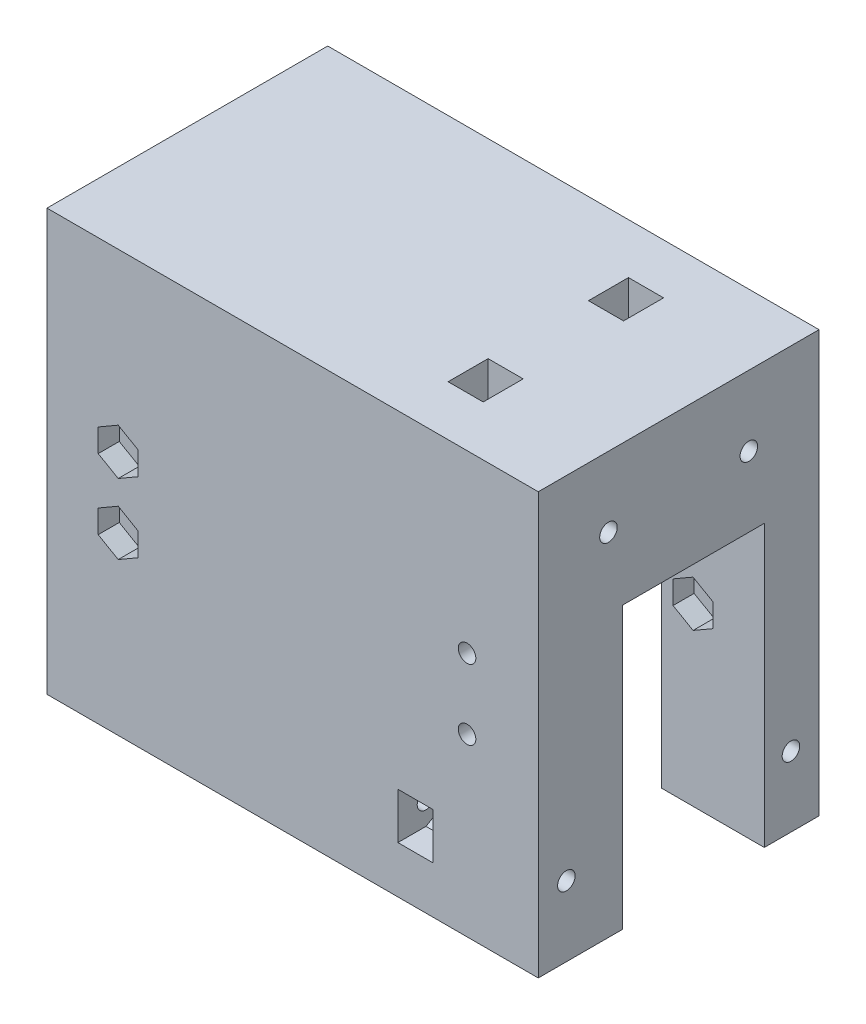
SolidWorks part; units mm, degrees
ref_plane "正面" through (0, 0, 0) normal (0, 0, 1) x (1, 0, 0)
ref_plane "平面" through (0, 0, 0) normal (0, 1, 0) x (1, 0, 0)
ref_plane "右側面" through (0, 0, 0) normal (1, 0, 0) x (0, 0, -1)
sketch "ｽｹｯﾁ2" plane through (0, 0, 0) normal (0, 0, 1) x (1, 0, 0)
  line L1 (-35, 30) -> (35, 30)
  line L2 (-35, 30) -> (-35, -30)
  line L3 (-35, -30) -> (35, -30)
  line L4 (35, 30) -> (35, -30)
  line L5 (-35, 30) -> (35, -30) construction
  line L6 (-35, -30) -> (35, 30) construction
  line L11 (-1.1602, 0.9945) -> (26.8884, -23.0472) construction
  line L12 (-15.8388, -9.5033) -> (15.8388, 9.5033) construction
  point P0 (0, 0)
  point P6 (0, 0)
  dimension "D1" = 70
  dimension "D2" = 60
extrude "ﾎﾞｽ - 押し出し2" add sketch "ｽｹｯﾁ2" along normal blind 40
sketch "ｽｹｯﾁ3" plane through (0, 0, 0) normal (0, 0, 1) x (1, 0, 0)
  line L1 (-20.35, 10.25) -> (20.35, 10.25)
  line L2 (-20.35, 10.25) -> (-20.35, -10.25)
  line L3 (-20.35, -10.25) -> (20.35, -10.25)
  line L4 (20.35, 10.25) -> (20.35, -10.25)
  line L5 (-20.35, 10.25) -> (20.35, -10.25) construction
  line L6 (-20.35, -10.25) -> (20.35, 10.25) construction
  point P0 (0, 0)
  dimension "D1" = 40.7
  dimension "D2" = 20.5
extrude "ｶｯﾄ - 押し出し1" cut sketch "ｽｹｯﾁ3" along normal blind 28 contours L2 L1 L4 L3
sketch "ｽｹｯﾁ4" plane through (0, 0, 0) normal (0, 0, 1) x (1, 0, 0)
  line L0 (20.35, 10.25) -> (35, 10.25)
  line L1 (35, -30) -> (35, 30) construction
  line L2 (35, 10.25) -> (35, -10.25)
  line L3 (35, -10.25) -> (20.35, -10.25)
  line L4 (20.35, -10.25) -> (20.35, 10.25)
extrude "ﾎﾞｽ - 押し出し3" add sketch "ｽｹｯﾁ4" along normal blind 28
sketch "ｽｹｯﾁ5" plane through (0, 0, 0) normal (0, 0, 1) x (1, 0, 0)
  line L0 (20.35, 10.25) -> (35, 10.25)
  line L1 (35, -30) -> (35, 30) construction
  line L2 (35, 10.25) -> (35, -10.25)
  line L3 (35, -10.25) -> (20.35, -10.25)
  line L4 (20.35, -10.25) -> (20.35, 10.25)
sketch "ｽｹｯﾁ6" plane through (0, 0, 0) normal (0, 0, 1) x (1, 0, 0)
  line L0 (-25, -30) -> (-25, -25)
  line L1 (-35, -30) -> (35, -30) construction
  line L2 (-25, -25) -> (-15, -25)
  line L3 (-15, -25) -> (-15, -30)
  line L4 (-15, -30) -> (-25, -30)
  line L5 (15, -25) -> (15, -30)
  line L6 (15, -30) -> (25, -30)
  line L7 (25, -30) -> (25, -25)
  line L8 (25, -25) -> (15, -25)
  dimension "D1" = 15
  dimension "D2" = 10
  dimension "D3" = 15
  dimension "D4" = 10
  dimension "D5" = 5
  dimension "D6" = 5
sketch "ｽｹｯﾁ8" plane through (0, 0, 0) normal (0, 0, 1) x (1, 0, 0)
  line L0 (-25, 30) -> (-25, 25)
  line L1 (35, 30) -> (-35, 30) construction
  line L2 (-25, 25) -> (-15, 25)
  line L3 (-15, 25) -> (-15, 30)
  line L4 (-15, 30) -> (-25, 30)
  line L5 (15, 30) -> (15, 25)
  line L6 (15, 25) -> (25, 25)
  line L7 (25, 25) -> (25, 30)
  line L8 (25, 30) -> (15, 30)
  dimension "D1" = 15
  dimension "D2" = 10
  dimension "D3" = 5
  dimension "D4" = 5
  dimension "D5" = 10
  dimension "D6" = 10
  dimension "D7" = 15
sketch "ｽｹｯﾁ15" plane through (0, 0, 0) normal (0, 0, 1) x (1, 0, 0)
  line L0 (-20.35, 10.25) -> (-20.35, -30)
  line L1 (-15, -30) -> (-25, -30) construction
  line L2 (-20.35, -30) -> (20.35, -30)
  line L3 (15, -30) -> (25, -30) construction
  line L4 (20.35, -30) -> (20.35, 10.25)
  line L5 (20.35, 10.25) -> (-20.35, 10.25)
extrude "ｶｯﾄ - 押し出し6" cut sketch "ｽｹｯﾁ15" along normal blind 28
ref_plane "平面1" through (0, -30, 0) normal (0, -1, 0) x (-1, 0, 0)
sketch "ｽｹｯﾁ16" plane through (0, -30, 0) normal (0, -1, 0) x (-1, 0, 0)
  line L0 (-20.35, -28) -> (-35, -28)
  line L1 (-35, -40) -> (-35, 0) construction
  line L2 (-35, -28) -> (-35, -7.7959)
  line L3 (-35, -7.7959) -> (-20.35, -7.7959)
  line L4 (-20.35, -28) -> (-20.35, 0) construction
  line L5 (-20.35, -7.7959) -> (-20.35, -28)
extrude "ｶｯﾄ - 押し出し7" cut sketch "ｽｹｯﾁ16" against normal blind 40
hole_wizard "M3x0.5 ねじ穴2" positions "ｽｹｯﾁ12" profile "ｽｹｯﾁ13" tap size "M3x0.5" standard "JIS" end condition through all
sketch "ｽｹｯﾁ12" plane through (0, 0, 0) normal (0, 0, -1) x (-1, 0, 0)
  line L0 (20.35, 10.25) -> (20.35, -30) construction
  point P0 (24.85, 5)
  point P2 (24.85, -5)
  dimension "D1" = 10
  dimension "D2" = 5
  dimension "D3" = 24.85
  dimension "D4" = 4.5
sketch "ｽｹｯﾁ13" plane through (-24.85, 5, 0) normal (1, 0, 0) x (0, 1, 0)
  line L0 (0, 0) -> (0, 40)
  line L1 (0, 40) -> (1.25, 40)
  line L2 (1.25, 40) -> (1.25, 0)
  line L5 (1.25, 0) -> (0, 0)
  line L11 (0, -6.35) -> (0, 107.95) construction
  dimension "次ｻｰﾌｪｽまでのねじ下穴ﾄﾞﾘﾙ直径" = 2.5
  dimension "次ｻｰﾌｪｽまでのねじ下穴ﾄﾞﾘﾙの深さ" = 40
cosmetic thread "穴のねじ山3" parameters "D2"=3
cosmetic thread "穴のねじ山4" parameters "D2"=3
mirror "ﾐﾗｰ1" about plane through (0, 0, 0) normal (1, 0, 0) of "M3x0.5 ねじ穴2"
cosmetic thread "穴のねじ山5" parameters "D2"=3
cosmetic thread "穴のねじ山6" parameters "D2"=3
sketch "ｽｹｯﾁ17" plane through (0, 0, 40) normal (0, 0, 1) x (1, 0, 0)
  line L0 (-24.85, 5) -> (-24.85, -5) construction
  line L2 (-24.85, 8.2909) -> (-27.7, 6.6454)
  line L3 (-27.7, 6.6454) -> (-27.7, 3.3546)
  line L4 (-27.7, 3.3546) -> (-24.85, 1.7091)
  line L5 (-24.85, 1.7091) -> (-22, 3.3546)
  line L6 (-22, 3.3546) -> (-22, 6.6454)
  line L7 (-22, 6.6454) -> (-24.85, 8.2909)
  line L8 (-22, -6.6454) -> (-22, -3.3546)
  line L9 (-22, -3.3546) -> (-24.85, -1.7091)
  line L10 (-24.85, -1.7091) -> (-27.7, -3.3546)
  line L11 (-27.7, -3.3546) -> (-27.7, -6.6454)
  line L12 (-27.7, -6.6454) -> (-24.85, -8.2909)
  line L13 (-24.85, -8.2909) -> (-22, -6.6454)
  circle A0 centre (-24.85, 5) radius 2.85 construction
  circle A1 centre (-24.85, -5) radius 2.85 construction
  dimension "D1" = 5.7
  dimension "5.7" = 5.7
extrude "ｶｯﾄ - 押し出し8" cut sketch "ｽｹｯﾁ17" against normal blind 3
sketch "ｽｹｯﾁ18" plane through (0, 0, 7.7959) normal (0, 0, 1) x (1, 0, 0)
  line L0 (24.85, -5) -> (24.85, 5) construction
  line L2 (27.7, 3.3546) -> (27.7, 6.6454)
  line L3 (27.7, 6.6454) -> (24.85, 8.2909)
  line L4 (24.85, 8.2909) -> (22, 6.6454)
  line L5 (22, 6.6454) -> (22, 3.3546)
  line L6 (22, 3.3546) -> (24.85, 1.7091)
  line L7 (24.85, 1.7091) -> (27.7, 3.3546)
  line L8 (27.7, -6.6454) -> (27.7, -3.3546)
  line L9 (27.7, -3.3546) -> (24.85, -1.7091)
  line L10 (24.85, -1.7091) -> (22, -3.3546)
  line L11 (22, -3.3546) -> (22, -6.6454)
  line L12 (22, -6.6454) -> (24.85, -8.2909)
  line L13 (24.85, -8.2909) -> (27.7, -6.6454)
  circle A0 centre (24.85, 5) radius 2.85 construction
  circle A1 centre (24.85, -5) radius 2.85 construction
  dimension "D1" = 5.7
  dimension "D2" = 5.7
extrude "ｶｯﾄ - 押し出し9" cut sketch "ｽｹｯﾁ18" against normal blind 3
ref_plane "平面2" through (0, 0, 20) normal (0, 0, -1) x (-1, 0, 0)
sketch "ｽｹｯﾁ19" plane through (0, 0, 20) normal (0, 0, -1) x (-1, 0, 0)
  line L0 (24.85, -5) -> (24.85, 5) construction
  line L1 (24.85, 1.7091) -> (35, 1.7091)
  line L2 (24.85, 1.7091) -> (27.7, 3.3546)
  line L3 (27.7, 3.3546) -> (27.7, 6.6454)
  line L4 (27.7, 6.6454) -> (24.85, 8.2909)
  line L5 (24.85, 8.2909) -> (22, 6.6454)
  line L6 (22, 6.6454) -> (22, 3.3546)
  line L7 (22, 3.3546) -> (24.85, 1.7091)
  line L8 (27.7, -6.6454) -> (27.7, -3.3546)
  line L9 (27.7, -3.3546) -> (24.85, -1.7091)
  line L10 (24.85, -1.7091) -> (22, -3.3546)
  line L11 (22, -3.3546) -> (22, -6.6454)
  line L12 (22, -6.6454) -> (24.85, -8.2909)
  line L13 (24.85, -8.2909) -> (27.7, -6.6454)
  line L14 (35, 30) -> (35, -30) construction
  line L15 (35, 1.7091) -> (35, 8.2909)
  line L16 (35, 8.2909) -> (24.85, 8.2909)
  line L17 (24.85, -1.7091) -> (35, -1.7091)
  line L18 (35, -1.7091) -> (35, -8.2909)
  line L19 (35, -8.2909) -> (24.85, -8.2909)
  circle A0 centre (24.85, 5) radius 2.85 construction
  circle A1 centre (24.85, -5) radius 2.85 construction
  dimension "D1" = 5.7
  dimension "D2" = 5.7
extrude "ｶｯﾄ - 押し出し10" cut sketch "ｽｹｯﾁ19" against normal blind 6 contours L15 L16 L4 L3 L2 L1 | L6 L7 L2 L3 L4 L5 | L12 L13 L8 L9 L10 L11 | L19 L18 L17 L9 L8 L13
ref_plane "平面3" through (20, 0, 0) normal (1, 0, 0) x (0, 0, -1)
hole_wizard "M3x0.5 ねじ穴3" positions "ｽｹｯﾁ21" profile "ｽｹｯﾁ22" tap size "M3x0.5" standard "JIS"
sketch "ｽｹｯﾁ21" plane through (35, 0, 0) normal (1, 0, 0) x (0, 0, -1)
  line L0 (0, -30) -> (0, 30) construction
  line L1 (-40, 30) -> (0, 30) construction
  line L2 (-40, -30) -> (-40, 30) construction
  line L3 (-22, -30) -> (22, -30) construction
  point P0 (-4, -20)
  point P2 (-36, -20)
  point P4 (-10, 20)
  point P6 (-30, 20)
  dimension "D1" = 10
  dimension "D2" = 10
  dimension "D3" = 10
  dimension "D4" = 10
  dimension "D5" = 4
  dimension "D6" = 4
  dimension "D7" = 10
  dimension "D8" = 10
cosmetic thread "穴のねじ山7" parameters "D1"=14.65, "D2"=3
cosmetic thread "穴のねじ山8" parameters "D1"=14.65, "D2"=3
cosmetic thread "穴のねじ山9" parameters "D1"=14.65, "D2"=3
cosmetic thread "穴のねじ山10" parameters "D1"=14.65, "D2"=3
sketch "ｽｹｯﾁ22" plane through (35, -20, 4) normal (0, 1, 0) x (0, 0, -1)
  line L0 (0, 0) -> (0, 40.7511)
  line L1 (0, 40.7511) -> (1.25, 40)
  line L2 (1.25, 40) -> (1.25, 0)
  line L5 (1.25, 0) -> (0, 0)
  line L10 (0, 40.7511) -> (-1.25, 40) construction
  line L11 (0, -6.35) -> (0, 107.95) construction
  dimension "ねじ下穴ﾄﾞﾘﾙ直径" = 2.5
  dimension "ねじ下穴ﾄﾞﾘﾙの深さ" = 40
  dimension "ﾄﾞﾘﾙ角度" = 118
sketch "ｽｹｯﾁ23" plane through (0, 0, 0) normal (1, 0, 0) x (0, 0, -1)
  line L0 (-40, -30) -> (-40, 30) construction
  line L1 (-33.15, -21.6454) -> (-33.15, -18.3546)
  line L2 (-33.15, -18.3546) -> (-36, -16.7091)
  line L3 (-36, -16.7091) -> (-38.85, -18.3546)
  line L4 (-38.85, -18.3546) -> (-38.85, -21.6454)
  line L5 (-38.85, -21.6454) -> (-36, -23.2909)
  line L6 (-36, -23.2909) -> (-33.15, -21.6454)
  line L7 (-4, -23.2909) -> (-1.15, -21.6454)
  line L8 (-1.15, -21.6454) -> (-1.15, -18.3546)
  line L9 (-1.15, -18.3546) -> (-4, -16.7091)
  line L10 (-4, -16.7091) -> (-6.85, -18.3546)
  line L11 (-6.85, -18.3546) -> (-6.85, -21.6454)
  line L12 (-6.85, -21.6454) -> (-4, -23.2909)
  line L13 (-30, 16.7091) -> (-27.15, 18.3546)
  line L14 (-27.15, 18.3546) -> (-27.15, 21.6454)
  line L15 (-27.15, 21.6454) -> (-30, 23.2909)
  line L16 (-30, 23.2909) -> (-32.85, 21.6454)
  line L17 (-32.85, 21.6454) -> (-32.85, 18.3546)
  line L18 (-32.85, 18.3546) -> (-30, 16.7091)
  line L19 (-7.15, 18.3546) -> (-7.15, 21.6454)
  line L20 (-7.15, 21.6454) -> (-10, 23.2909)
  line L21 (-10, 23.2909) -> (-12.85, 21.6454)
  line L22 (-12.85, 21.6454) -> (-12.85, 18.3546)
  line L23 (-12.85, 18.3546) -> (-10, 16.7091)
  line L24 (-10, 16.7091) -> (-7.15, 18.3546)
  line L25 (0, -30) -> (0, 30) construction
  line L27 (-7.7959, 10) -> (-7.7959, -30) construction
  line L28 (-32.85, 21.6454) -> (-32.85, 30)
  line L29 (-40, 30) -> (0, 30) construction
  line L30 (-32.85, 30) -> (-27.15, 30)
  line L31 (-27.15, 30) -> (-27.15, 21.6454)
  line L32 (-12.85, 21.6454) -> (-12.85, 30)
  line L33 (-12.85, 30) -> (-7.15, 30)
  line L34 (-7.15, 30) -> (-7.15, 21.6454)
  line L35 (-36, -23.2909) -> (-40, -23.2909)
  line L36 (-40, -23.2909) -> (-40, -16.7091)
  line L37 (-40, -16.7091) -> (-36, -16.7091)
  circle A0 centre (-36, -20) radius 2.85 construction
  circle A1 centre (-4, -20) radius 2.85 construction
  circle A2 centre (-30, 20) radius 2.85 construction
  circle A3 centre (-10, 20) radius 2.85 construction
  point P42 (0, 0)
  dimension "D1" = 5.7
  dimension "D2" = 5.7
  dimension "D3" = 5.7
  dimension "D4" = 5.7
sketch "ｽｹｯﾁ24" plane through (20, 0, 0) normal (1, 0, 0) x (0, 0, -1)
  line L0 (-40, -30) -> (-40, 30) construction
  line L1 (-30, 16.7091) -> (-27.15, 18.3546)
  line L2 (-27.15, 18.3546) -> (-27.15, 21.6454)
  line L3 (-27.15, 21.6454) -> (-30, 23.2909)
  line L4 (-30, 23.2909) -> (-32.85, 21.6454)
  line L5 (-32.85, 21.6454) -> (-32.85, 18.3546)
  line L6 (-32.85, 18.3546) -> (-30, 16.7091)
  line L7 (-10, 16.7091) -> (-7.15, 18.3546)
  line L8 (-7.15, 18.3546) -> (-7.15, 21.6454)
  line L9 (-7.15, 21.6454) -> (-10, 23.2909)
  line L10 (-10, 23.2909) -> (-12.85, 21.6454)
  line L11 (-12.85, 21.6454) -> (-12.85, 18.3546)
  line L12 (-12.85, 18.3546) -> (-10, 16.7091)
  line L13 (-36, -23.2909) -> (-33.15, -21.6454)
  line L14 (-33.15, -21.6454) -> (-33.15, -18.3546)
  line L15 (-33.15, -18.3546) -> (-36, -16.7091)
  line L16 (-36, -16.7091) -> (-38.85, -18.3546)
  line L17 (-38.85, -18.3546) -> (-38.85, -21.6454)
  line L18 (-38.85, -21.6454) -> (-36, -23.2909)
  line L19 (-4, -23.2909) -> (-1.15, -21.6454)
  line L20 (-1.15, -21.6454) -> (-1.15, -18.3546)
  line L21 (-1.15, -18.3546) -> (-4, -16.7091)
  line L22 (-4, -16.7091) -> (-6.85, -18.3546)
  line L23 (-6.85, -18.3546) -> (-6.85, -21.6454)
  line L24 (-6.85, -21.6454) -> (-4, -23.2909)
  line L25 (-40, -23.2909) -> (-40, -16.7091) construction
  line L26 (0, -30) -> (0, 30) construction
  line L27 (-32.85, 18.3546) -> (-32.85, 30)
  line L28 (-32.85, 30) -> (-27.15, 30)
  line L29 (-27.15, 30) -> (-27.15, 21.6454)
  line L30 (-27.15, 21.6454) -> (-27.15, 18.3546)
  line L31 (-12.85, 18.3546) -> (-12.85, 30)
  line L32 (-12.85, 30) -> (-7.15, 30)
  line L33 (-7.15, 30) -> (-7.15, 21.6454)
  line L34 (-7.15, 21.6454) -> (-7.15, 18.3546)
  line L35 (-36, -16.7091) -> (-40, -16.7091)
  line L36 (-40, -16.7091) -> (-40, -23.2909)
  line L37 (-40, -23.2909) -> (-36, -23.2909)
  line L38 (-36, -23.2909) -> (-33.15, -21.6454)
  line L39 (-4, -23.2909) -> (0, -23.2909)
  line L40 (0, -23.2909) -> (0, -16.7091)
  line L41 (0, -16.7091) -> (-4, -16.7091)
  circle A0 centre (-30, 20) radius 2.85 construction
  circle A1 centre (-10, 20) radius 2.85 construction
  circle A2 centre (-36, -20) radius 2.85 construction
  circle A3 centre (-4, -20) radius 2.85 construction
  dimension "D1" = 5.7
  dimension "D2" = 5.7
  dimension "D3" = 5.7
  dimension "D4" = 5.7
extrude "ｶｯﾄ - 押し出し12" cut sketch "ｽｹｯﾁ24" against normal blind 5 contours L17 L18 L13 L14 L15 L16 | L36 L37 L18 L17 L16 L35 | L23 L24 L19 L20 L21 L22 | L33 L32 L31 L10 L9 | L11 L12 L7 L8 L9 L10 | L5 L6 L1 L2 L3 L4 | L29 L28 L27 L4 L3 | L40 L41 L21 L20 L19 L39
